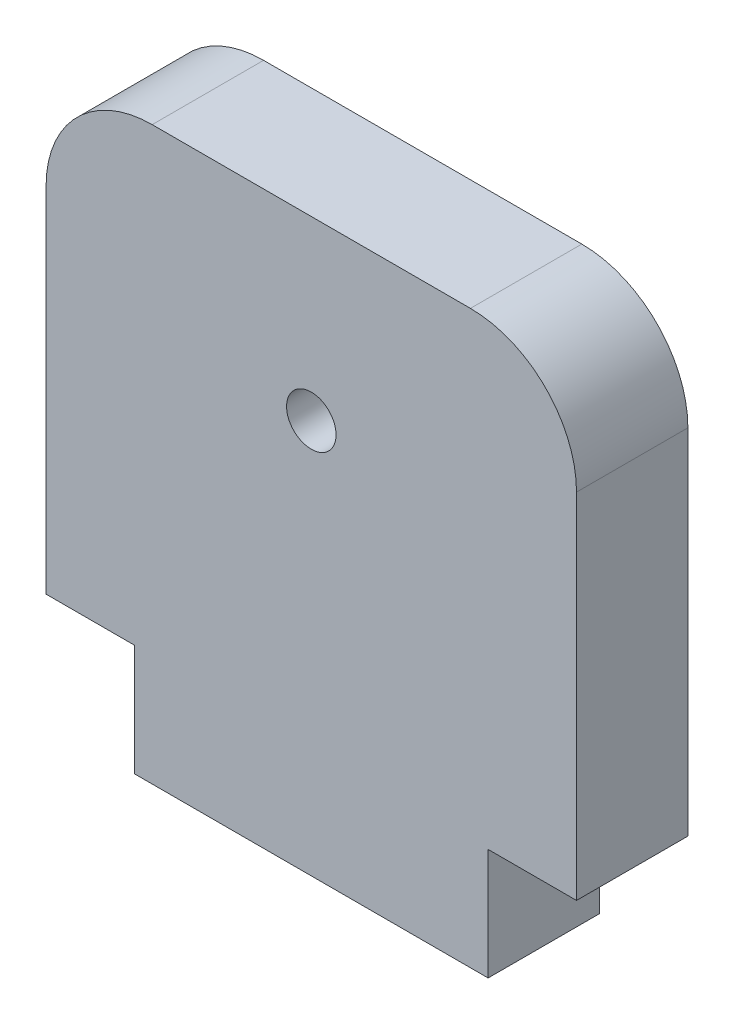
SolidWorks part; units mm, degrees
material "Hexcel AS4C (3000 Filaments)"
ref_plane "Front Plane" through (0, 0, 0) normal (0, 0, 1) x (1, 0, 0)
ref_plane "Top Plane" through (0, 0, 0) normal (0, 1, 0) x (1, 0, 0)
ref_plane "Right Plane" through (0, 0, 0) normal (1, 0, 0) x (0, 0, -1)
sketch "Sketch2" plane through (0, 0, 0) normal (0, 0, 1) x (1, 0, 0)
  line L0 (-9.525, -8.255) -> (-6.35, -8.255)
  line L1 (-9.525, -8.255) -> (9.525, -8.255) construction
  line L2 (-9.525, -8.255) -> (-9.525, 4.445)
  line L3 (-5.715, 8.255) -> (5.715, 8.255)
  line L4 (9.525, -8.255) -> (9.525, 4.445)
  line L5 (-9.525, -8.255) -> (9.525, 8.255) construction
  line L6 (-9.525, 8.255) -> (9.525, -8.255) construction
  line L7 (-6.35, -8.255) -> (-6.35, -12.255)
  line L8 (-6.35, -12.255) -> (6.35, -12.255)
  line L9 (6.35, -12.255) -> (6.35, -8.255)
  line L10 (6.35, -8.255) -> (9.525, -8.255)
  arc A1 (5.715, 8.255) -> (9.525, 4.445) centre (5.715, 4.445) cw
  arc A2 (-9.525, 4.445) -> (-5.715, 8.255) centre (-5.715, 4.445) cw
  circle A3 centre (0, 1.905) radius 0.889
  point P0 (0, 0)
  point P19 (0, 8.255)
  dimension "D3" = 1.778
  dimension "D6" = 3.81
  dimension "D1" = 16.51
  dimension "D2" = 19.05
  dimension "D4" = 4
  dimension "D5" = 12.7
  dimension "D7" = 6.35
extrude "Boss-Extrude1" add sketch "Sketch2" along normal blind 4
